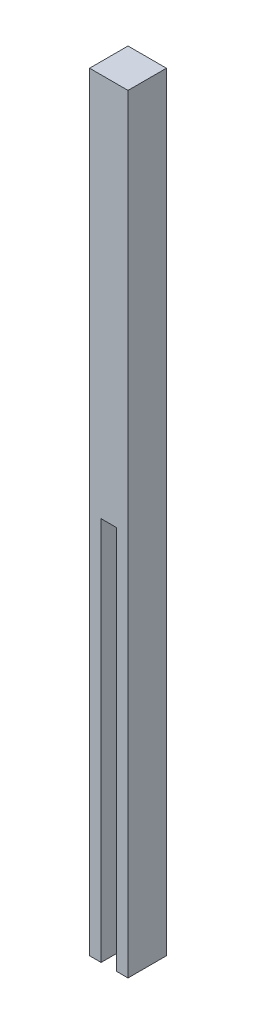
SolidWorks part; units mm, degrees
ref_plane "Front Plane" through (0, 0, 0) normal (0, 0, 1) x (1, 0, 0)
ref_plane "Top Plane" through (0, 0, 0) normal (0, 1, 0) x (1, 0, 0)
ref_plane "Right Plane" through (0, 0, 0) normal (1, 0, 0) x (0, 0, -1)
sketch "Sketch1" plane through (0, 0, 0) normal (0, 1, 0) x (1, 0, 0)
  line L1 (-43.4919, 32.6944) -> (56.5081, 32.6944)
  line L2 (-43.4919, 32.6944) -> (-43.4919, -67.3056)
  line L3 (-43.4919, -67.3056) -> (56.5081, -67.3056)
  line L4 (56.5081, 32.6944) -> (56.5081, -67.3056)
  dimension "D2" = 100
extrude "Boss-Extrude1" add sketch "Sketch1" along normal blind 2000
sketch "Sketch2" plane through (0, 0, 67.3056) normal (0, 0, 1) x (1, 0, 0)
  line L0 (-43.4919, 2000) -> (-43.4919, 0) construction
  line L1 (-13.4919, 1000) -> (26.5081, 1000)
  line L2 (-13.4919, 1000) -> (-13.4919, 0)
  line L3 (-13.4919, 0) -> (26.5081, 0)
  line L4 (26.5081, 1000) -> (26.5081, 0)
  line L5 (-43.4919, 0) -> (56.5081, 0) construction
  dimension "D1" = 1000
  dimension "D2" = 40
  dimension "D3" = 30
  dimension "D4" = 0
extrude "Cut-Extrude1" cut sketch "Sketch2" against normal blind 40 contours L1 L4 L3 L2
equation "\"BeamWidth\"= 100"
equation "\"BeamLength\"= 100"
equation "\"BeamHeight\"= 2000"
equation "\"D1@Sketch1\"=\"BeamWidth\""
equation "\"D2@Sketch1\"=\"BeamLength\""
equation "\"D1@Boss-Extrude1\"=\"BeamHeight\""
equation "\"LegHeight\"= 1000"
equation "\"LegScannerWidth\"= 40"
equation "\"D1@Sketch2\"=\"LegHeight\""
equation "\"D2@Sketch2\"=\"LegScannerWidth\""
equation "\"D3@Sketch2\"=(\"BeamWidth\"-\"LegScannerWidth\")/2"
equation "\"LegScannerDepth\"= 40"
equation "\"D1@Cut-Extrude1\"=\"LegScannerDepth\""
